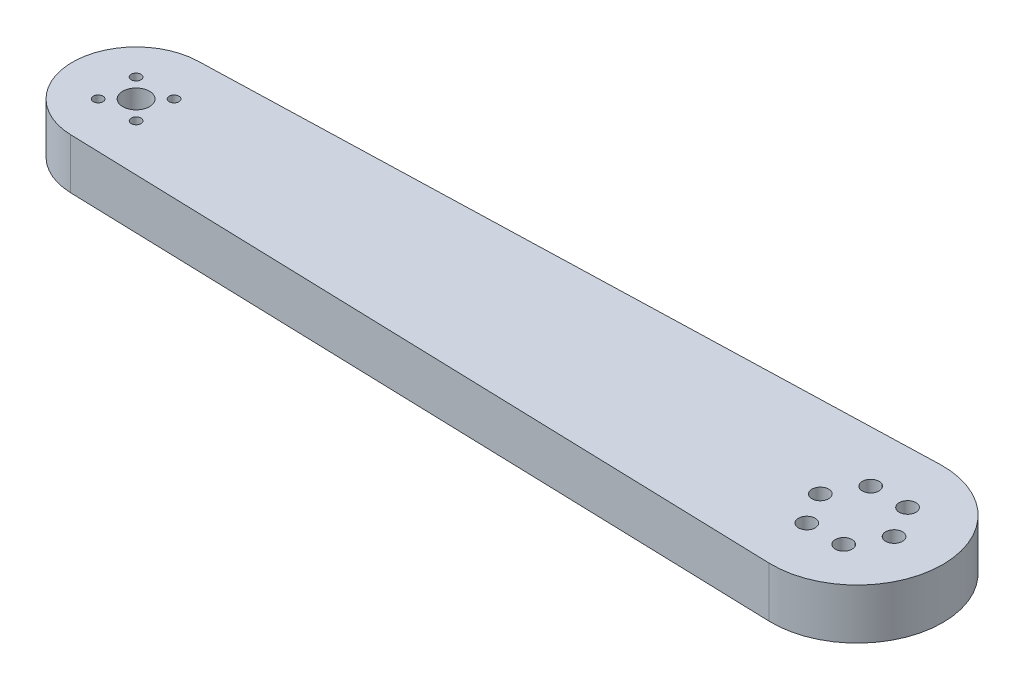
SolidWorks part; units mm, degrees
ref_plane "前视基准面" through (0, 0, 0) normal (0, 0, 1) x (1, 0, 0)
ref_plane "上视基准面" through (0, 0, 0) normal (0, 1, 0) x (1, 0, 0)
ref_plane "右视基准面" through (0, 0, 0) normal (1, 0, 0) x (0, 0, -1)
sketch "草图1" plane through (0, 0, 0) normal (0, 1, 0) x (1, 0, 0)
  line L0 (0, 0) -> (136.444, 0) construction
  line L1 (-0.5744, 18.9913) -> (214.2291, 25.4883)
  line L2 (-0.5744, -18.9913) -> (214.2291, -25.4883)
  line L4 (220.5, -9.5263) -> (226, 0) construction
  line L5 (226, 0) -> (220.5, 9.5263) construction
  line L6 (220.5, 9.5263) -> (209.5, 9.5263) construction
  line L7 (209.5, 9.5263) -> (204, 0) construction
  line L8 (204, 0) -> (209.5, -9.5263) construction
  line L9 (209.5, -9.5263) -> (220.5, -9.5263) construction
  line L10 (-5.6569, -5.6569) -> (5.6569, -5.6569) construction
  line L11 (5.6569, -5.6569) -> (5.6569, 5.6569) construction
  line L12 (5.6569, 5.6569) -> (-5.6569, 5.6569) construction
  line L13 (-5.6569, 5.6569) -> (-5.6569, -5.6569) construction
  circle A0 centre (0, 0) radius 4
  circle A1 centre (0, 0) radius 19 construction
  circle A3 centre (215, 0) radius 25.5 construction
  arc A4 (214.2291, 25.4883) -> (214.2291, -25.4883) centre (215, 0) cw
  arc A5 (-0.5744, 18.9913) -> (-0.5744, -18.9913) centre (0, 0) ccw
  circle A6 centre (215, 0) radius 11 construction
  circle A7 centre (215, 0) radius 9.5263 construction
  circle A8 centre (209.5, 9.5263) radius 2.5
  circle A9 centre (220.5, 9.5263) radius 2.5
  circle A10 centre (226, 0) radius 2.5
  circle A11 centre (220.5, -9.5263) radius 2.5
  circle A12 centre (209.5, -9.5263) radius 2.5
  circle A13 centre (204, 0) radius 2.5
  circle A14 centre (0, 0) radius 8 construction
  circle A15 centre (0, 0) radius 5.6569 construction
  circle A16 centre (-5.6569, 5.6569) radius 1.45
  circle A17 centre (5.6569, 5.6569) radius 1.45
  circle A18 centre (5.6569, -5.6569) radius 1.45
  circle A19 centre (-5.6569, -5.6569) radius 1.45
  dimension "D1" = 8
  dimension "D2" = 38
  dimension "D3" = 22
  dimension "D5" = 51
  dimension "D6" = 5
  dimension "D7" = 16
  dimension "D8" = 2.9
  dimension "D4" = 215
extrude "凸台-拉伸1" add sketch "草图1" along normal blind 15
chamfer "倒角1" distance 1.8 angle 45 4 edges at (-5.6569, 0, 7.1069) (5.6569, 0, 7.1069) (-5.6569, 0, -4.2069) (5.6569, 0, -4.2069)
chamfer "倒角2" distance 2.7 angle 45 3 edges at (226, 0, 2.5) (209.5, 0, -7.0263) (209.5, 0, 12.0263)
